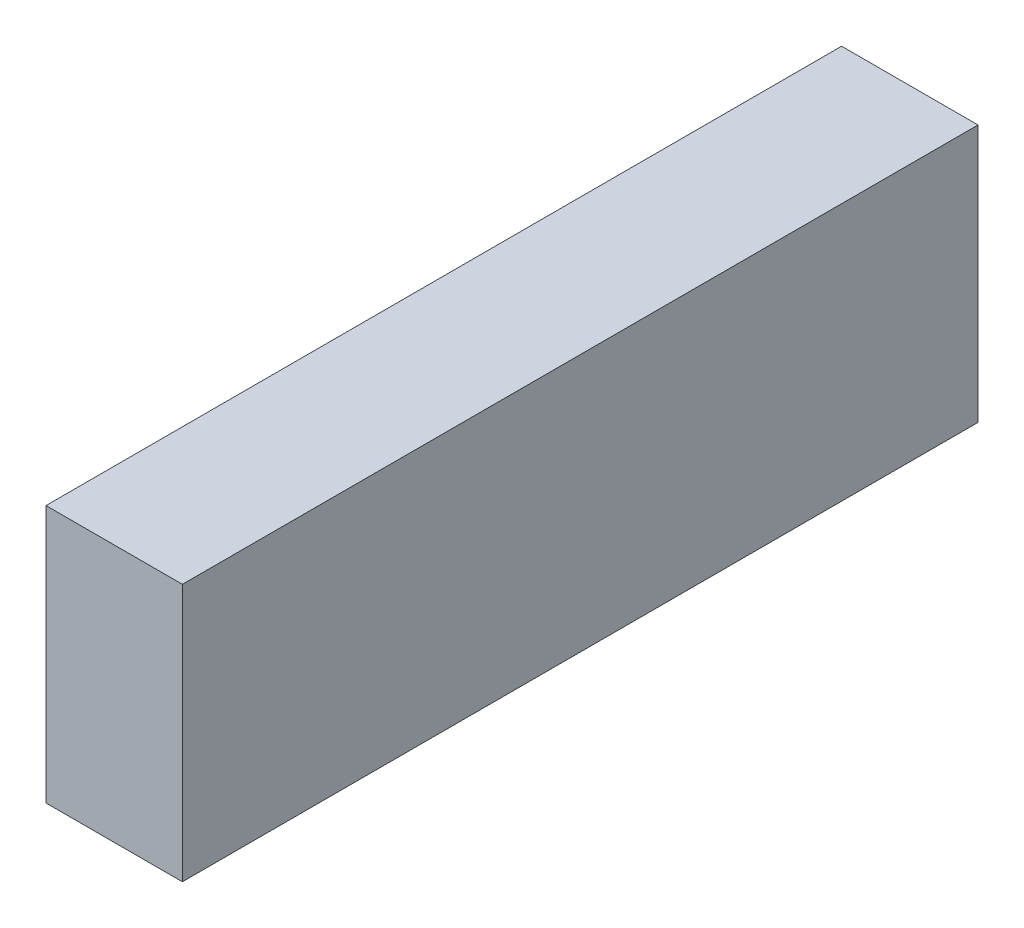
SolidWorks part; units mm, degrees
ref_plane "Plan de face" through (0, 0, 0) normal (0, 0, 1) x (1, 0, 0)
ref_plane "Plan de dessus" through (0, 0, 0) normal (0, 1, 0) x (1, 0, 0)
ref_plane "Plan de droite" through (0, 0, 0) normal (1, 0, 0) x (0, 0, -1)
sketch "Esquisse1" plane through (0, 0, 0) normal (0, 0, 1) x (1, 0, 0)
  line L1 (0, 0) -> (18, 0)
  line L2 (0, 0) -> (0, 34)
  line L3 (0, 34) -> (18, 34)
  line L4 (18, 0) -> (18, 34)
  dimension "D1" = 18
  dimension "D2" = 34
extrude "Boss.-Extru.1" add sketch "Esquisse1" along normal blind 105 contours L2 L3 L4 L1
